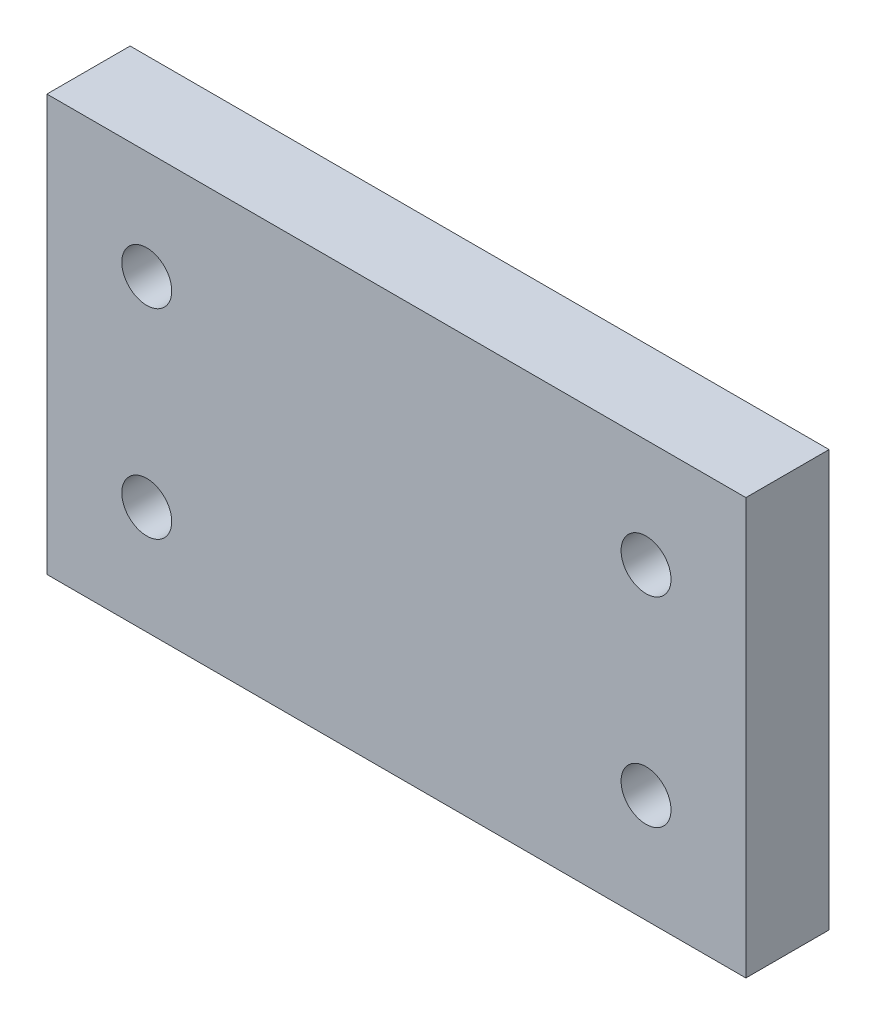
SolidWorks part; units mm, degrees
ref_plane "前视基准面" through (0, 0, 0) normal (0, 0, 1) x (1, 0, 0)
ref_plane "上视基准面" through (0, 0, 0) normal (0, 1, 0) x (1, 0, 0)
ref_plane "右视基准面" through (0, 0, 0) normal (1, 0, 0) x (0, 0, -1)
other "Configuration Table"
sketch "草图1" plane through (0, 0, 0) normal (0, 0, 1) x (1, 0, 0)
  line L1 (21, -12.5) -> (-21, -12.5)
  line L2 (21, -12.5) -> (21, 12.5)
  line L3 (21, 12.5) -> (-21, 12.5)
  line L4 (-21, -12.5) -> (-21, 12.5)
  line L5 (21, -12.5) -> (-21, 12.5) construction
  line L6 (21, 12.5) -> (-21, -12.5) construction
  line L7 (15, -6) -> (-15, -6) construction
  line L8 (15, -6) -> (15, 6) construction
  line L9 (15, 6) -> (-15, 6) construction
  line L10 (-15, -6) -> (-15, 6) construction
  line L11 (15, -6) -> (-15, 6) construction
  line L12 (15, 6) -> (-15, -6) construction
  circle A0 centre (15, 6) radius 1.5
  circle A1 centre (15, -6) radius 1.5
  circle A2 centre (-15, -6) radius 1.5
  circle A3 centre (-15, 6) radius 1.5
  point P0 (0, 0)
  point P5 (0, 0)
  dimension "D3" = 3
  dimension "D1" = 42
  dimension "D2" = 25
  dimension "D4" = 30
  dimension "D5" = 12
extrude "凸台-拉伸1" add sketch "草图1" along normal blind 5
